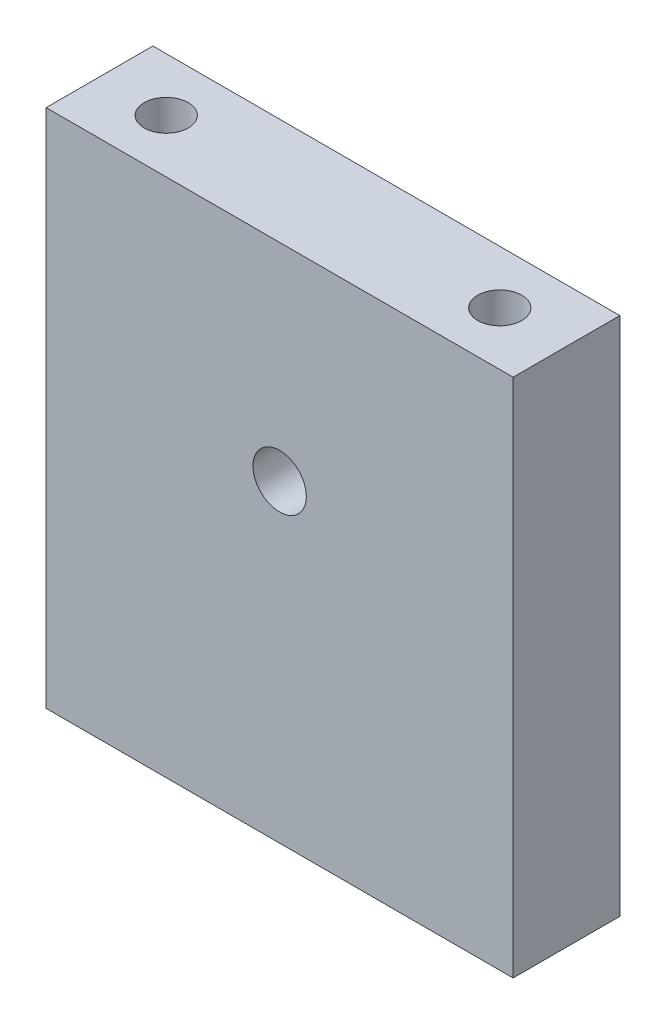
SolidWorks part; units mm, degrees
material "6061-T6 (SS)"
ref_plane "前视基准面" through (0, 0, 0) normal (0, 0, 1) x (1, 0, 0)
ref_plane "上视基准面" through (0, 0, 0) normal (0, 1, 0) x (1, 0, 0)
ref_plane "右视基准面" through (0, 0, 0) normal (1, 0, 0) x (0, 0, -1)
sketch "草图1" plane through (0, 0, 0) normal (0, 0, 1) x (1, 0, 0)
  line L0 (17.5, 39) -> (17.5, 23.5) construction
  line L1 (0, 0) -> (35, 0)
  line L2 (0, 0) -> (0, 39)
  line L3 (0, 39) -> (35, 39)
  line L4 (35, 0) -> (35, 39)
  circle A0 centre (17.5, 23.5) radius 2
  dimension "D3" = 4
  dimension "D1" = 39
  dimension "D2" = 35
  dimension "D4" = 15.5
extrude "凸台-拉伸1" add sketch "草图1" along normal blind 8
cosmetic thread "装饰螺纹线5" parameters "D2"=5
sketch "草图2" plane through (0, 39, 0) normal (0, 1, 0) x (1, 0, 0)
  line L0 (0, -4) -> (5, -4) construction
  line L1 (0, -8) -> (0, 0) construction
  line L2 (5, -4) -> (30, -4) construction
  line L3 (30, -4) -> (35, -4) construction
  line L4 (35, -8) -> (35, 0) construction
  circle A0 centre (5, -4) radius 1.65
  circle A1 centre (30, -4) radius 1.65
  dimension "D2" = 3.3
  dimension "D1" = 25
extrude "切除-拉伸1" cut sketch "草图2" against normal through all
cosmetic thread "装饰螺纹线1" parameters "D2"=4
cosmetic thread "装饰螺纹线2" parameters "D2"=4
cosmetic thread "装饰螺纹线3" parameters "D2"=4
cosmetic thread "装饰螺纹线4" parameters "D2"=4
